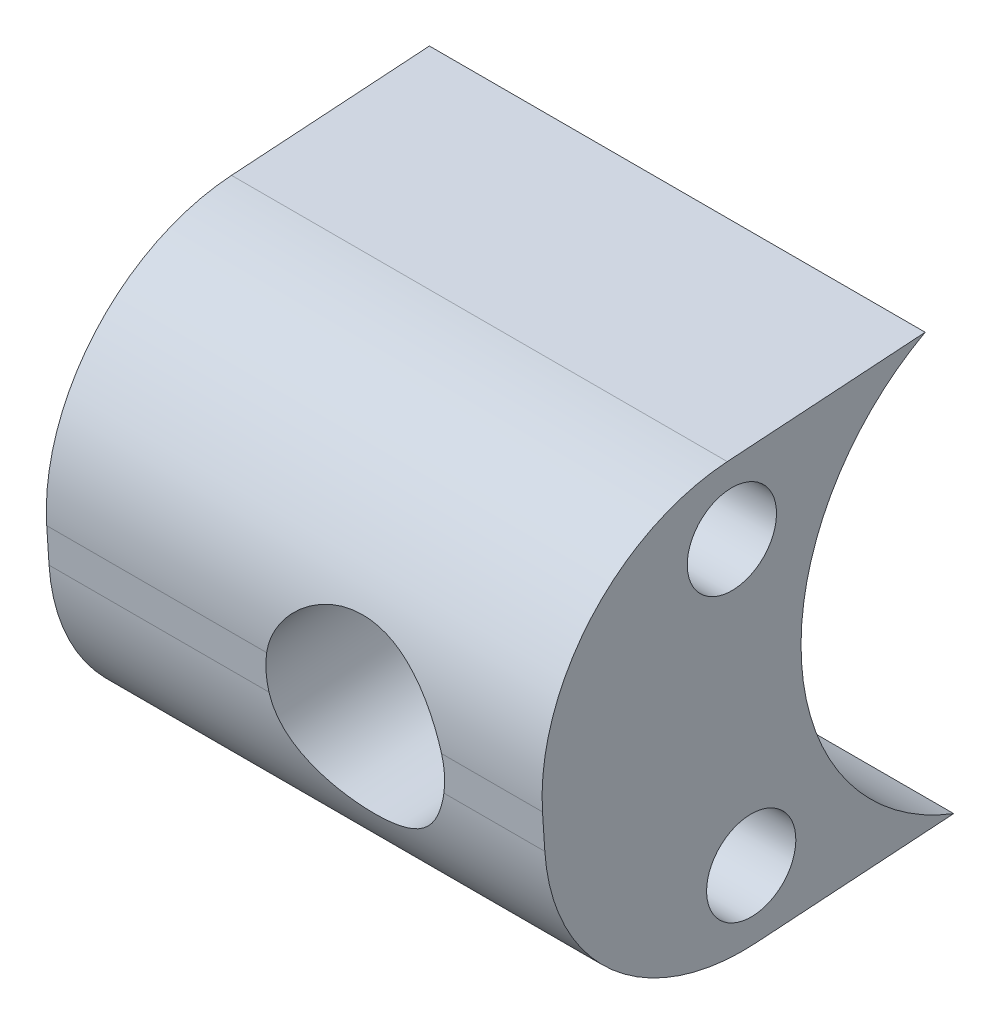
SolidWorks part; units mm, degrees
ref_plane "Front Plane" through (0, 0, 0) normal (0, 0, 1) x (1, 0, 0)
ref_plane "Top Plane" through (0, 0, 0) normal (0, 1, 0) x (1, 0, 0)
ref_plane "Right Plane" through (0, 0, 0) normal (1, 0, 0) x (0, 0, -1)
sketch "Sketch1" plane through (-10, 0, 0) normal (1, 0, 0) x (0, 0, -1)
  line L0 (-95.1013, 44.1738) -> (-95.2193, 45.9576) construction
  line L1 (-95.1013, 44.1738) -> (-95.2193, 45.9576)
  line L2 (-74.4849, 35.5156) -> (-84.4631, 34.8556) construction
  line L3 (-85.9011, 56.5958) -> (-75.9229, 57.2559) construction
  line L4 (-74.4849, 35.5156) -> (-84.4631, 34.8556)
  line L5 (-85.9011, 56.5958) -> (-75.9229, 57.2559)
  arc A0 (-95.1013, 44.1738) -> (-84.4631, 34.8556) centre (-85.1231, 44.8338) ccw construction
  arc A1 (-85.9011, 56.5958) -> (-95.2193, 45.9576) centre (-85.2411, 46.6176) ccw construction
  arc A2 (-95.1013, 44.1738) -> (-84.4631, 34.8556) centre (-85.1231, 44.8338) ccw
  arc A3 (-85.9011, 56.5958) -> (-95.2193, 45.9576) centre (-85.2411, 46.6176) ccw
  arc A5 (-75.9229, 57.2559) -> (-74.4849, 35.5156) centre (-70.1826, 46.7179) ccw
extrude "Boss-Extrude1" add sketch "Sketch1" along normal blind 25
sketch "Sketch2" plane through (0, 0.2166, -6.5555) normal (0, -0.066, 0.9978) x (1, 0, 0)
  line L0 (-14.5, 51.4648) -> (15, 51.4648) construction
  circle A0 centre (5.5, 51.4648) radius 4.5
  point P6 (0, 0)
  point P7 (-14.5, 52.3586)
  point P9 (0, 0)
  dimension "D2" = 9
  dimension "D1" = 20
extrude "Cut-Extrude1" cut sketch "Sketch2" against normal through all both and the other way through all
sketch "Sketch4" plane through (-10, 0, 0) normal (-1, 0, 0) x (0, 0, 1)
  circle A0 centre (85.6695, 53.094) radius 1
  circle A1 centre (84.6947, 38.3574) radius 1
extrude "Cut-Extrude3" cut sketch "Sketch4" against normal through all
sketch "Sketch5" plane through (15, 0, 0) normal (1, 0, 0) x (0, 0, -1)
  circle A0 centre (-84.6947, 38.3574) radius 2.25
  circle A1 centre (-85.6695, 53.094) radius 2.25
  dimension "D1" = 4.5
extrude "Cut-Extrude4" cut sketch "Sketch5" against normal blind 13
